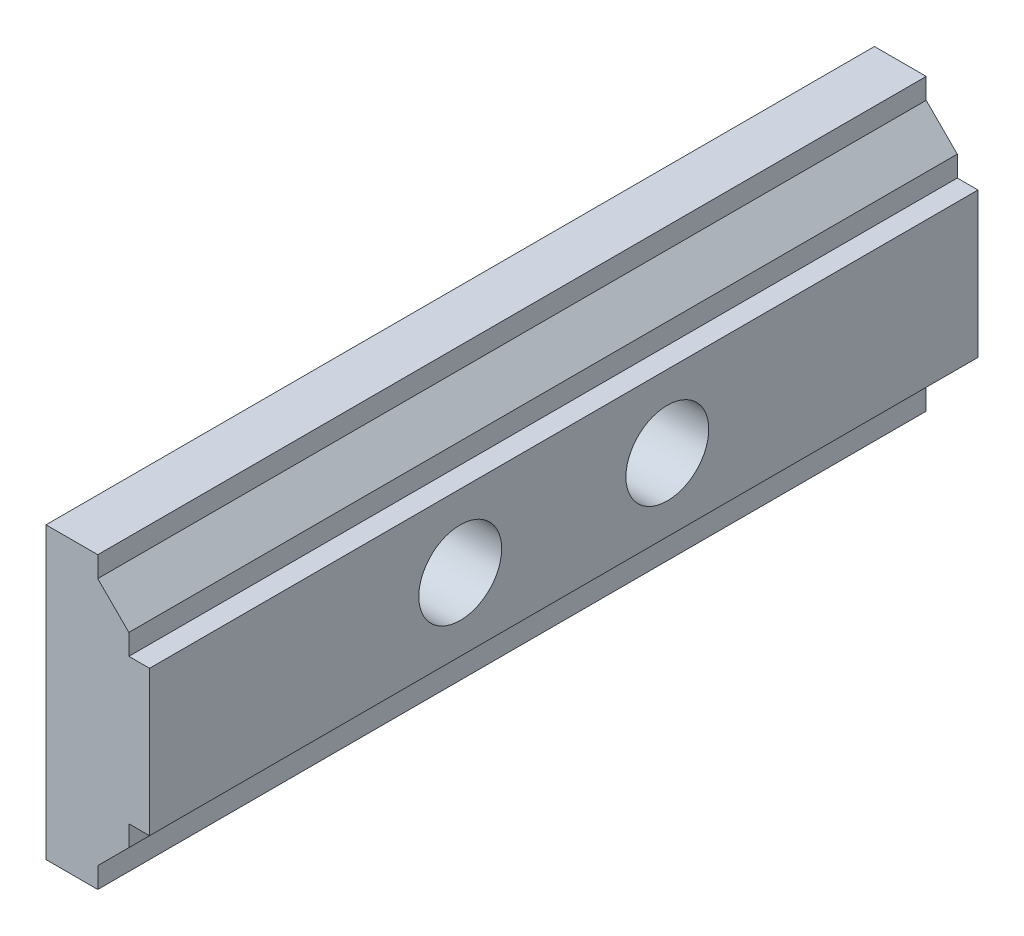
SolidWorks part; units mm, degrees
ref_plane "Plano frontal" through (0, 0, 0) normal (0, 0, 1) x (1, 0, 0)
ref_plane "Plano superior" through (0, 0, 0) normal (0, 1, 0) x (1, 0, 0)
ref_plane "Plano direito" through (0, 0, 0) normal (1, 0, 0) x (0, 0, -1)
sketch "Esboço1" plane through (0, 0, 0) normal (1, 0, 0) x (0, 0, -1)
  line L0 (30, 6) -> (-30, -6) construction
  line L1 (-30, 6) -> (30, 6)
  line L2 (-30, 6) -> (-30, -6)
  line L3 (-30, -6) -> (30, -6)
  line L4 (30, 6) -> (30, -6)
  dimension "D1" = 12
  dimension "D2" = 60
extrude "Ressalto-extrusão1" add sketch "Esboço1" along normal blind 4
sketch "Esboço3" plane through (0, 0, 0) normal (-1, 0, 0) x (0, 0, 1)
  line L0 (-30, 6) -> (30, 6) construction
  line L1 (30, -6) -> (5, -6)
  line L2 (30, -6) -> (30, 6)
  line L3 (30, 6) -> (5, 6)
  line L4 (5, -6) -> (5, 6)
  dimension "D1" = 25
extrude "Corte-extrusão2" cut sketch "Esboço3" against normal blind 10
sketch "Esboço4" plane through (0, 0, 0) normal (-1, 0, 0) x (0, 0, 1)
  line L1 (-30, 6) -> (-35, 6)
  line L2 (-30, 6) -> (-30, -6)
  line L3 (-30, -6) -> (-35, -6)
  line L4 (-35, 6) -> (-35, -6)
  dimension "D1" = 5
extrude "Ressalto-extrusão2" add sketch "Esboço4" against normal up to surface (4 mm away) up to face at (4, 0, -12.5)
sketch "Esboço5" plane through (0, 0, 5) normal (0, 0, 1) x (1, 0, 0)
  line L0 (4, 6) -> (2.5, 6)
  line L1 (4, 6) -> (0, 6) construction
  line L2 (2.5, 6) -> (4, 4.5)
  line L3 (4, -6) -> (4, 6) construction
  line L4 (4, 4.5) -> (4, 6)
  line L5 (4, 0) -> (2.5, 0) construction
  line L6 (4, -4.5) -> (4, -6)
  line L7 (2.5, -6) -> (4, -4.5)
  line L8 (4, -6) -> (2.5, -6)
  dimension "D1" = 1.5
  dimension "D2" = 1.5
extrude "Corte-extrusão3" cut sketch "Esboço5" against normal through all
sketch "Esboço6" plane through (4, 0, 0) normal (1, 0, 0) x (0, 0, -1)
  line L0 (-5, -4.5) -> (-5, 4.5) construction
  line L1 (-5, 3.5) -> (35, 3.5)
  line L2 (-5, 3.5) -> (-5, -3.5)
  line L3 (-5, -3.5) -> (35, -3.5)
  line L4 (35, 3.5) -> (35, -3.5)
  line L5 (35, 4.5) -> (35, -4.5) construction
  line L6 (35, 4.5) -> (-5, 4.5) construction
  line L7 (35, -4.5) -> (-5, -4.5) construction
  dimension "D1" = 1
  dimension "D2" = 1
extrude "Ressalto-extrusão3" add sketch "Esboço6" along normal blind 1
sketch "Esboço2" plane through (0, 0, 0) normal (-1, 0, 0) x (0, 0, 1)
  line L0 (-30, 0) -> (30, 0) construction
  line L3 (-30, 0) -> (-35, 0) construction
  line L4 (-35, 6) -> (-35, -6) construction
  circle A0 centre (-20, 0) radius 2
  circle A2 centre (-10, 0) radius 2
  dimension "D1" = 4
  dimension "D2" = 10
  dimension "D3" = 10
extrude "Corte-extrusão1" cut sketch "Esboço2" against normal blind 15
sketch "Esboço7" plane through (0, 0, -35) normal (0, 0, -1) x (-1, 0, 0)
  line L0 (0, 0) -> (-1.2889, 0) construction
  line L1 (-2.5, 6) -> (0, 6)
  line L2 (-2.5, 6) -> (-2.5, 7)
  line L3 (-2.5, 7) -> (0, 7)
  line L4 (0, 6) -> (0, 7)
  line L5 (0, 6) -> (0, -6) construction
  line L6 (-2.5, -6) -> (-2.5, -7)
  line L7 (-2.5, -6) -> (0, -6)
  line L8 (0, -6) -> (0, -7)
  line L9 (-2.5, -7) -> (0, -7)
  dimension "D1" = 1
extrude "Ressalto-extrusão4" add sketch "Esboço7" against normal up to surface (40 mm away) up to face at (3.2, -0.1, 5)
